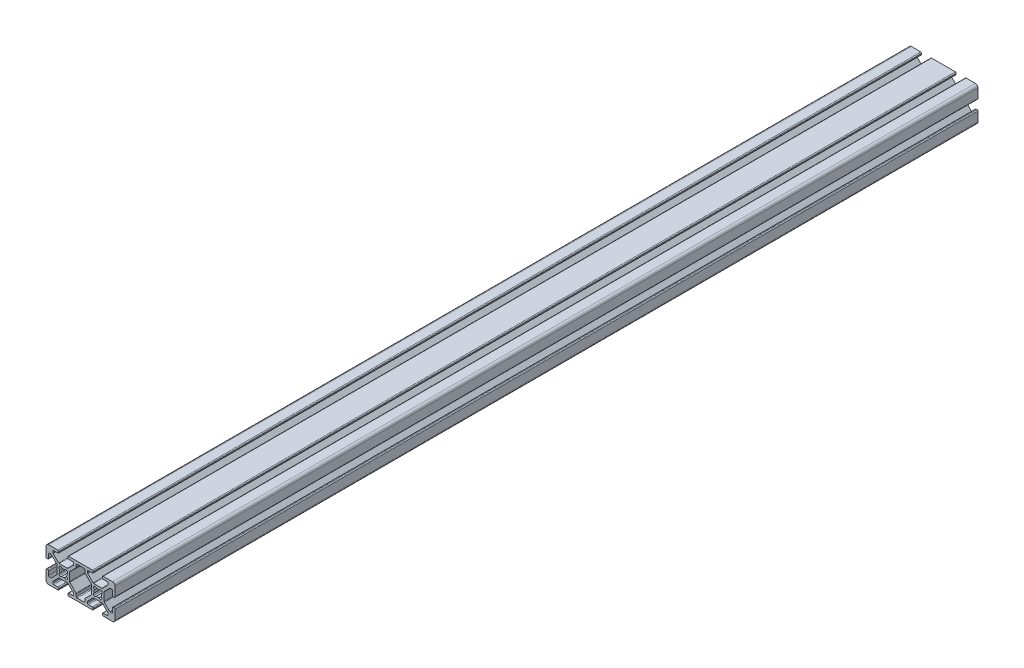
SolidWorks part; units mm, degrees
ref_plane "Front Plane" through (0, 0, 0) normal (0, 0, 1) x (1, 0, 0)
ref_plane "Top Plane" through (0, 0, 0) normal (0, 1, 0) x (1, 0, 0)
ref_plane "Right Plane" through (0, 0, 0) normal (1, 0, 0) x (0, 0, -1)
sketch "Sketch1" plane through (0, 0, 0) normal (0, 0, 1) x (1, 0, 0)
  line L0 (-16.6492, -61.9845) -> (-16.8288, -61.8049)
  line L1 (-16.8288, -57.5551) -> (-16.6492, -57.3755)
  line L2 (-12.3994, -57.3755) -> (-12.2198, -57.5551)
  line L3 (-12.2198, -61.8049) -> (-12.3994, -61.9845)
  line L4 (-27.0293, -67.672) -> (-27.0293, -66.3248)
  line L5 (-27.1781, -65.9655) -> (-30.7205, -62.4231)
  line L6 (-30.8693, -62.0639) -> (-30.8693, -57.2961)
  line L7 (-30.7205, -56.9369) -> (-27.1781, -53.3944)
  line L8 (-27.0293, -53.0352) -> (-27.0293, -51.688)
  line L9 (-26.5213, -51.18) -> (-22.5273, -51.18)
  line L10 (-22.0193, -51.688) -> (-22.0193, -53.0352)
  line L11 (-21.8705, -53.3944) -> (-18.3281, -56.9369)
  line L12 (-18.1793, -57.2961) -> (-18.1793, -62.0639)
  line L13 (-18.3281, -62.4231) -> (-21.8705, -65.9655)
  line L14 (-22.0193, -66.3248) -> (-22.0193, -67.672)
  line L15 (-22.5273, -68.18) -> (-26.5213, -68.18)
  line L16 (-36.6492, -61.9845) -> (-36.8288, -61.8049)
  line L17 (-36.8288, -57.5551) -> (-36.6492, -57.3755)
  line L18 (-32.3994, -57.3755) -> (-32.2198, -57.5551)
  line L19 (-32.2198, -61.8049) -> (-32.3994, -61.9845)
  line L20 (-36.9082, -63.335) -> (-32.1404, -63.335)
  line L21 (-31.7812, -63.4838) -> (-28.6781, -66.5869)
  line L22 (-28.5293, -66.9461) -> (-28.5293, -67.672)
  line L23 (-29.0373, -68.18) -> (-31.3863, -68.18)
  line L24 (-31.8943, -68.688) -> (-31.8943, -69.172)
  line L25 (-31.3863, -69.68) -> (-17.6623, -69.68)
  line L26 (-17.1543, -69.172) -> (-17.1543, -68.688)
  line L27 (-17.6623, -68.18) -> (-20.0113, -68.18)
  line L28 (-20.5193, -67.672) -> (-20.5193, -66.9461)
  line L29 (-20.3705, -66.5869) -> (-17.2674, -63.4838)
  line L30 (-16.9082, -63.335) -> (-12.1404, -63.335)
  line L31 (-11.7812, -63.4838) -> (-8.6781, -66.5869)
  line L32 (-8.5293, -66.9461) -> (-8.5293, -67.672)
  line L33 (-9.0373, -68.18) -> (-11.3863, -68.18)
  line L34 (-11.8943, -68.688) -> (-11.8943, -69.172)
  line L35 (-11.3863, -69.68) -> (-6.0243, -69.68)
  line L36 (-4.5243, -68.18) -> (-4.5243, -62.818)
  line L37 (-5.0323, -62.31) -> (-5.5163, -62.31)
  line L38 (-6.0243, -62.818) -> (-6.0243, -65.167)
  line L39 (-6.5323, -65.675) -> (-7.2582, -65.675)
  line L40 (-7.6174, -65.5262) -> (-10.7205, -62.4231)
  line L41 (-10.8693, -62.0639) -> (-10.8693, -57.2961)
  line L42 (-10.7205, -56.9369) -> (-7.6174, -53.8338)
  line L43 (-7.2582, -53.685) -> (-6.5323, -53.685)
  line L44 (-6.0243, -54.193) -> (-6.0243, -56.542)
  line L45 (-5.5163, -57.05) -> (-5.0323, -57.05)
  line L46 (-4.5243, -56.542) -> (-4.5243, -51.18)
  line L47 (-6.0243, -49.68) -> (-11.3863, -49.68)
  line L48 (-11.8943, -50.188) -> (-11.8943, -50.672)
  line L49 (-11.3863, -51.18) -> (-9.0373, -51.18)
  line L50 (-8.5293, -51.688) -> (-8.5293, -52.4139)
  line L51 (-8.6781, -52.7731) -> (-11.7812, -55.8762)
  line L52 (-12.1404, -56.025) -> (-16.9082, -56.025)
  line L53 (-17.2674, -55.8762) -> (-20.3705, -52.7731)
  line L54 (-20.5193, -52.4139) -> (-20.5193, -51.688)
  line L55 (-20.0113, -51.18) -> (-17.6623, -51.18)
  line L56 (-17.1543, -50.672) -> (-17.1543, -50.188)
  line L57 (-17.6623, -49.68) -> (-31.3863, -49.68)
  line L58 (-31.8943, -50.188) -> (-31.8943, -50.672)
  line L59 (-31.3863, -51.18) -> (-29.0373, -51.18)
  line L60 (-28.5293, -51.688) -> (-28.5293, -52.4139)
  line L61 (-28.6781, -52.7731) -> (-31.7812, -55.8762)
  line L62 (-32.1404, -56.025) -> (-36.9082, -56.025)
  line L63 (-37.2674, -55.8762) -> (-40.3705, -52.7731)
  line L64 (-40.5193, -52.4139) -> (-40.5193, -51.688)
  line L65 (-40.0113, -51.18) -> (-37.6623, -51.18)
  line L66 (-37.1543, -50.672) -> (-37.1543, -50.188)
  line L67 (-37.6623, -49.68) -> (-43.0243, -49.68)
  line L68 (-44.5243, -51.18) -> (-44.5243, -56.542)
  line L69 (-44.0163, -57.05) -> (-43.5323, -57.05)
  line L70 (-43.0243, -56.542) -> (-43.0243, -54.193)
  line L71 (-42.5163, -53.685) -> (-41.7904, -53.685)
  line L72 (-41.4312, -53.8338) -> (-38.3281, -56.9369)
  line L73 (-38.1793, -57.2961) -> (-38.1793, -62.0639)
  line L74 (-38.3281, -62.4231) -> (-41.4312, -65.5262)
  line L75 (-41.7904, -65.675) -> (-42.5163, -65.675)
  line L76 (-43.0243, -65.167) -> (-43.0243, -62.818)
  line L77 (-43.5323, -62.31) -> (-44.0163, -62.31)
  line L78 (-44.5243, -62.818) -> (-44.5243, -68.18)
  line L79 (-43.0243, -69.68) -> (-37.6623, -69.68)
  line L80 (-37.1543, -69.172) -> (-37.1543, -68.688)
  line L81 (-37.6623, -68.18) -> (-40.0113, -68.18)
  line L82 (-40.5193, -67.672) -> (-40.5193, -66.9461)
  line L83 (-40.3705, -66.5869) -> (-37.2674, -63.4838)
  arc A0 (-16.4594, -60.484) -> (-16.8288, -61.8049) centre (-16.2723, -61.2484) ccw
  arc A1 (-16.4594, -58.876) -> (-16.4594, -60.484) centre (-14.5243, -59.68) ccw
  arc A2 (-16.8288, -57.5551) -> (-16.4594, -58.876) centre (-16.2723, -58.1116) ccw
  arc A3 (-15.3283, -57.7449) -> (-16.6492, -57.3755) centre (-16.0927, -57.932) ccw
  arc A4 (-13.7203, -57.7449) -> (-15.3283, -57.7449) centre (-14.5243, -59.68) ccw
  arc A5 (-12.3994, -57.3755) -> (-13.7203, -57.7449) centre (-12.9559, -57.932) ccw
  arc A6 (-12.5892, -58.876) -> (-12.2198, -57.5551) centre (-12.7763, -58.1116) ccw
  arc A7 (-12.5892, -60.484) -> (-12.5892, -58.876) centre (-14.5243, -59.68) ccw
  arc A8 (-12.2198, -61.8049) -> (-12.5892, -60.484) centre (-12.7763, -61.2484) ccw
  arc A9 (-13.7203, -61.6151) -> (-12.3994, -61.9845) centre (-12.9559, -61.428) ccw
  arc A10 (-15.3283, -61.6151) -> (-13.7203, -61.6151) centre (-14.5243, -59.68) ccw
  arc A11 (-16.6492, -61.9845) -> (-15.3283, -61.6151) centre (-16.0927, -61.428) ccw
  arc A12 (-27.0293, -67.672) -> (-26.5213, -68.18) centre (-26.5213, -67.672) ccw
  arc A13 (-27.0293, -66.3248) -> (-27.1781, -65.9655) centre (-27.5373, -66.3248) ccw
  arc A14 (-30.8693, -62.0639) -> (-30.7205, -62.4231) centre (-30.3613, -62.0639) ccw
  arc A15 (-30.7205, -56.9369) -> (-30.8693, -57.2961) centre (-30.3613, -57.2961) ccw
  arc A16 (-27.1781, -53.3944) -> (-27.0293, -53.0352) centre (-27.5373, -53.0352) ccw
  arc A17 (-26.5213, -51.18) -> (-27.0293, -51.688) centre (-26.5213, -51.688) ccw
  arc A18 (-22.0193, -51.688) -> (-22.5273, -51.18) centre (-22.5273, -51.688) ccw
  arc A19 (-22.0193, -53.0352) -> (-21.8705, -53.3944) centre (-21.5113, -53.0352) ccw
  arc A20 (-18.1793, -57.2961) -> (-18.3281, -56.9369) centre (-18.6873, -57.2961) ccw
  arc A21 (-18.3281, -62.4231) -> (-18.1793, -62.0639) centre (-18.6873, -62.0639) ccw
  arc A22 (-21.8705, -65.9655) -> (-22.0193, -66.3248) centre (-21.5113, -66.3248) ccw
  arc A23 (-22.5273, -68.18) -> (-22.0193, -67.672) centre (-22.5273, -67.672) ccw
  arc A24 (-36.4594, -60.484) -> (-36.8288, -61.8049) centre (-36.2723, -61.2484) ccw
  arc A25 (-36.4594, -58.876) -> (-36.4594, -60.484) centre (-34.5243, -59.68) ccw
  arc A26 (-36.8288, -57.5551) -> (-36.4594, -58.876) centre (-36.2723, -58.1116) ccw
  arc A27 (-35.3283, -57.7449) -> (-36.6492, -57.3755) centre (-36.0927, -57.932) ccw
  arc A28 (-33.7203, -57.7449) -> (-35.3283, -57.7449) centre (-34.5243, -59.68) ccw
  arc A29 (-32.3994, -57.3755) -> (-33.7203, -57.7449) centre (-32.9559, -57.932) ccw
  arc A30 (-32.5892, -58.876) -> (-32.2198, -57.5551) centre (-32.7763, -58.1116) ccw
  arc A31 (-32.5892, -60.484) -> (-32.5892, -58.876) centre (-34.5243, -59.68) ccw
  arc A32 (-32.2198, -61.8049) -> (-32.5892, -60.484) centre (-32.7763, -61.2484) ccw
  arc A33 (-33.7203, -61.6151) -> (-32.3994, -61.9845) centre (-32.9559, -61.428) ccw
  arc A34 (-35.3283, -61.6151) -> (-33.7203, -61.6151) centre (-34.5243, -59.68) ccw
  arc A35 (-36.6492, -61.9845) -> (-35.3283, -61.6151) centre (-36.0927, -61.428) ccw
  arc A36 (-36.9082, -63.335) -> (-37.2674, -63.4838) centre (-36.9082, -63.843) ccw
  arc A37 (-31.7812, -63.4838) -> (-32.1404, -63.335) centre (-32.1404, -63.843) ccw
  arc A38 (-28.5293, -66.9461) -> (-28.6781, -66.5869) centre (-29.0373, -66.9461) ccw
  arc A39 (-29.0373, -68.18) -> (-28.5293, -67.672) centre (-29.0373, -67.672) ccw
  arc A40 (-31.3863, -68.18) -> (-31.8943, -68.688) centre (-31.3863, -68.688) ccw
  arc A41 (-31.8943, -69.172) -> (-31.3863, -69.68) centre (-31.3863, -69.172) ccw
  arc A42 (-17.6623, -69.68) -> (-17.1543, -69.172) centre (-17.6623, -69.172) ccw
  arc A43 (-17.1543, -68.688) -> (-17.6623, -68.18) centre (-17.6623, -68.688) ccw
  arc A44 (-20.5193, -67.672) -> (-20.0113, -68.18) centre (-20.0113, -67.672) ccw
  arc A45 (-20.3705, -66.5869) -> (-20.5193, -66.9461) centre (-20.0113, -66.9461) ccw
  arc A46 (-16.9082, -63.335) -> (-17.2674, -63.4838) centre (-16.9082, -63.843) ccw
  arc A47 (-11.7812, -63.4838) -> (-12.1404, -63.335) centre (-12.1404, -63.843) ccw
  arc A48 (-8.5293, -66.9461) -> (-8.6781, -66.5869) centre (-9.0373, -66.9461) ccw
  arc A49 (-9.0373, -68.18) -> (-8.5293, -67.672) centre (-9.0373, -67.672) ccw
  arc A50 (-11.3863, -68.18) -> (-11.8943, -68.688) centre (-11.3863, -68.688) ccw
  arc A51 (-11.8943, -69.172) -> (-11.3863, -69.68) centre (-11.3863, -69.172) ccw
  arc A52 (-6.0243, -69.68) -> (-4.5243, -68.18) centre (-6.0243, -68.18) ccw
  arc A53 (-4.5243, -62.818) -> (-5.0323, -62.31) centre (-5.0323, -62.818) ccw
  arc A54 (-5.5163, -62.31) -> (-6.0243, -62.818) centre (-5.5163, -62.818) ccw
  arc A55 (-6.5323, -65.675) -> (-6.0243, -65.167) centre (-6.5323, -65.167) ccw
  arc A56 (-7.6174, -65.5262) -> (-7.2582, -65.675) centre (-7.2582, -65.167) ccw
  arc A57 (-10.8693, -62.0639) -> (-10.7205, -62.4231) centre (-10.3613, -62.0639) ccw
  arc A58 (-10.7205, -56.9369) -> (-10.8693, -57.2961) centre (-10.3613, -57.2961) ccw
  arc A59 (-7.2582, -53.685) -> (-7.6174, -53.8338) centre (-7.2582, -54.193) ccw
  arc A60 (-6.0243, -54.193) -> (-6.5323, -53.685) centre (-6.5323, -54.193) ccw
  arc A61 (-6.0243, -56.542) -> (-5.5163, -57.05) centre (-5.5163, -56.542) ccw
  arc A62 (-5.0323, -57.05) -> (-4.5243, -56.542) centre (-5.0323, -56.542) ccw
  arc A63 (-4.5243, -51.18) -> (-6.0243, -49.68) centre (-6.0243, -51.18) ccw
  arc A64 (-11.3863, -49.68) -> (-11.8943, -50.188) centre (-11.3863, -50.188) ccw
  arc A65 (-11.8943, -50.672) -> (-11.3863, -51.18) centre (-11.3863, -50.672) ccw
  arc A66 (-8.5293, -51.688) -> (-9.0373, -51.18) centre (-9.0373, -51.688) ccw
  arc A67 (-8.6781, -52.7731) -> (-8.5293, -52.4139) centre (-9.0373, -52.4139) ccw
  arc A68 (-12.1404, -56.025) -> (-11.7812, -55.8762) centre (-12.1404, -55.517) ccw
  arc A69 (-17.2674, -55.8762) -> (-16.9082, -56.025) centre (-16.9082, -55.517) ccw
  arc A70 (-20.5193, -52.4139) -> (-20.3705, -52.7731) centre (-20.0113, -52.4139) ccw
  arc A71 (-20.0113, -51.18) -> (-20.5193, -51.688) centre (-20.0113, -51.688) ccw
  arc A72 (-17.6623, -51.18) -> (-17.1543, -50.672) centre (-17.6623, -50.672) ccw
  arc A73 (-17.1543, -50.188) -> (-17.6623, -49.68) centre (-17.6623, -50.188) ccw
  arc A74 (-31.3863, -49.68) -> (-31.8943, -50.188) centre (-31.3863, -50.188) ccw
  arc A75 (-31.8943, -50.672) -> (-31.3863, -51.18) centre (-31.3863, -50.672) ccw
  arc A76 (-28.5293, -51.688) -> (-29.0373, -51.18) centre (-29.0373, -51.688) ccw
  arc A77 (-28.6781, -52.7731) -> (-28.5293, -52.4139) centre (-29.0373, -52.4139) ccw
  arc A78 (-32.1404, -56.025) -> (-31.7812, -55.8762) centre (-32.1404, -55.517) ccw
  arc A79 (-37.2674, -55.8762) -> (-36.9082, -56.025) centre (-36.9082, -55.517) ccw
  arc A80 (-40.5193, -52.4139) -> (-40.3705, -52.7731) centre (-40.0113, -52.4139) ccw
  arc A81 (-40.0113, -51.18) -> (-40.5193, -51.688) centre (-40.0113, -51.688) ccw
  arc A82 (-37.6623, -51.18) -> (-37.1543, -50.672) centre (-37.6623, -50.672) ccw
  arc A83 (-37.1543, -50.188) -> (-37.6623, -49.68) centre (-37.6623, -50.188) ccw
  arc A84 (-43.0243, -49.68) -> (-44.5243, -51.18) centre (-43.0243, -51.18) ccw
  arc A85 (-44.5243, -56.542) -> (-44.0163, -57.05) centre (-44.0163, -56.542) ccw
  arc A86 (-43.5323, -57.05) -> (-43.0243, -56.542) centre (-43.5323, -56.542) ccw
  arc A87 (-42.5163, -53.685) -> (-43.0243, -54.193) centre (-42.5163, -54.193) ccw
  arc A88 (-41.4312, -53.8338) -> (-41.7904, -53.685) centre (-41.7904, -54.193) ccw
  arc A89 (-38.1793, -57.2961) -> (-38.3281, -56.9369) centre (-38.6873, -57.2961) ccw
  arc A90 (-38.3281, -62.4231) -> (-38.1793, -62.0639) centre (-38.6873, -62.0639) ccw
  arc A91 (-41.7904, -65.675) -> (-41.4312, -65.5262) centre (-41.7904, -65.167) ccw
  arc A92 (-43.0243, -65.167) -> (-42.5163, -65.675) centre (-42.5163, -65.167) ccw
  arc A93 (-43.0243, -62.818) -> (-43.5323, -62.31) centre (-43.5323, -62.818) ccw
  arc A94 (-44.0163, -62.31) -> (-44.5243, -62.818) centre (-44.0163, -62.818) ccw
  arc A95 (-44.5243, -68.18) -> (-43.0243, -69.68) centre (-43.0243, -68.18) ccw
  arc A96 (-37.6623, -69.68) -> (-37.1543, -69.172) centre (-37.6623, -69.172) ccw
  arc A97 (-37.1543, -68.688) -> (-37.6623, -68.18) centre (-37.6623, -68.688) ccw
  arc A98 (-40.5193, -67.672) -> (-40.0113, -68.18) centre (-40.0113, -67.672) ccw
  arc A99 (-40.3705, -66.5869) -> (-40.5193, -66.9461) centre (-40.0113, -66.9461) ccw
extrude "Extrude1" add sketch "Sketch1" along normal blind 500
